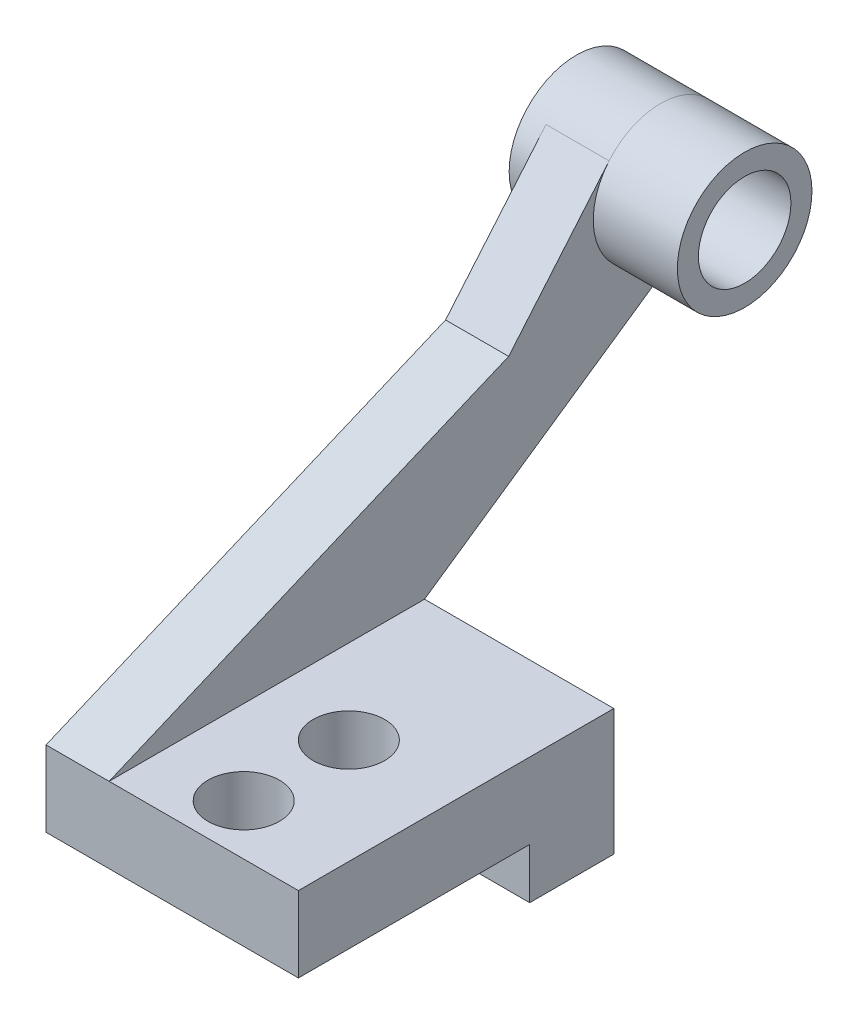
SolidWorks part; units mm, degrees
ref_plane "Front Plane" through (0, 0, 0) normal (0, 0, 1) x (1, 0, 0)
ref_plane "Top Plane" through (0, 0, 0) normal (0, 1, 0) x (1, 0, 0)
ref_plane "Right Plane" through (0, 0, 0) normal (1, 0, 0) x (0, 0, -1)
sketch "Sketch1" plane through (0, 0, 0) normal (1, 0, 0) x (0, 0, -1)
  line L0 (-29.3446, 0) -> (-29.3446, 18)
  line L1 (-29.3446, 18) -> (45.6554, 18)
  line L2 (45.6554, 18) -> (45.6554, -12)
  line L3 (45.6554, -12) -> (25.6554, -12)
  line L4 (25.6554, -12) -> (25.6554, 0)
  line L5 (25.6554, 0) -> (-29.3446, 0)
  point P2 (0, 0)
  point P7 (0, 0)
  dimension "D1" = 75
  dimension "D2" = 55
  dimension "D3" = 12
  dimension "D4" = 30
extrude "Boss-Extrude1" add sketch "Sketch1" against normal blind 60
sketch "Sketch2" plane through (-60, 0, 0) normal (-1, 0, 0) x (0, 0, 1)
  line L0 (29.3446, 18) -> (-65.6554, 58)
  line L3 (-45.6554, 18) -> (29.3446, 18)
  line L6 (-89.537, 86.3155) -> (-65.6554, 58)
  line L8 (-45.6554, 18) -> (-110.833, 62.8159)
  circle A0 centre (-101.7677, 76) radius 16
  circle A1 centre (-101.7677, 76) radius 11
  dimension "D3" = 32
  dimension "D1" = 58
  dimension "D2" = 95
  dimension "D4" = 58
extrude "Boss-Extrude2" add sketch "Sketch2" against normal blind 15
sketch "Sketch3" plane through (-45, 0, 0) normal (1, 0, 0) x (0, 0, -1)
  circle A0 centre (101.7677, 76) radius 16.0024
  circle A1 centre (101.7677, 76) radius 11
extrude "Boss-Extrude3" add sketch "Sketch3" along normal blind 20
sketch "Sketch4" plane through (-60, 0, 0) normal (-1, 0, 0) x (0, 0, 1)
  circle A0 centre (-101.7677, 76) radius 16
  circle A1 centre (-101.7677, 76) radius 11
extrude "Boss-Extrude4" add sketch "Sketch4" along normal blind 5
sketch "Sketch5" plane through (-45, 0, 0) normal (1, 0, 0) x (0, 0, -1)
  circle A0 centre (101.7677, 76) radius 11
extrude "Cut-Extrude2" cut sketch "Sketch5" against normal through all
sketch "Sketch6" plane through (0, 18, 0) normal (0, 1, 0) x (1, 0, 0)
  line L0 (-45, -29.3446) -> (0, -29.3446) construction
  line L1 (0, 45.6554) -> (0, -29.3446) construction
  circle A0 centre (-25, -17.3446) radius 8.5
  circle A1 centre (-25, 7.6554) radius 8.5
  point P4 (0, 0)
  point P6 (15.2188, 10.8116)
  dimension "D1" = 25
  dimension "D2" = 12
  dimension "D3" = 25
  dimension "D4" = 25
extrude "Cut-Extrude3" cut sketch "Sketch6" against normal through all
